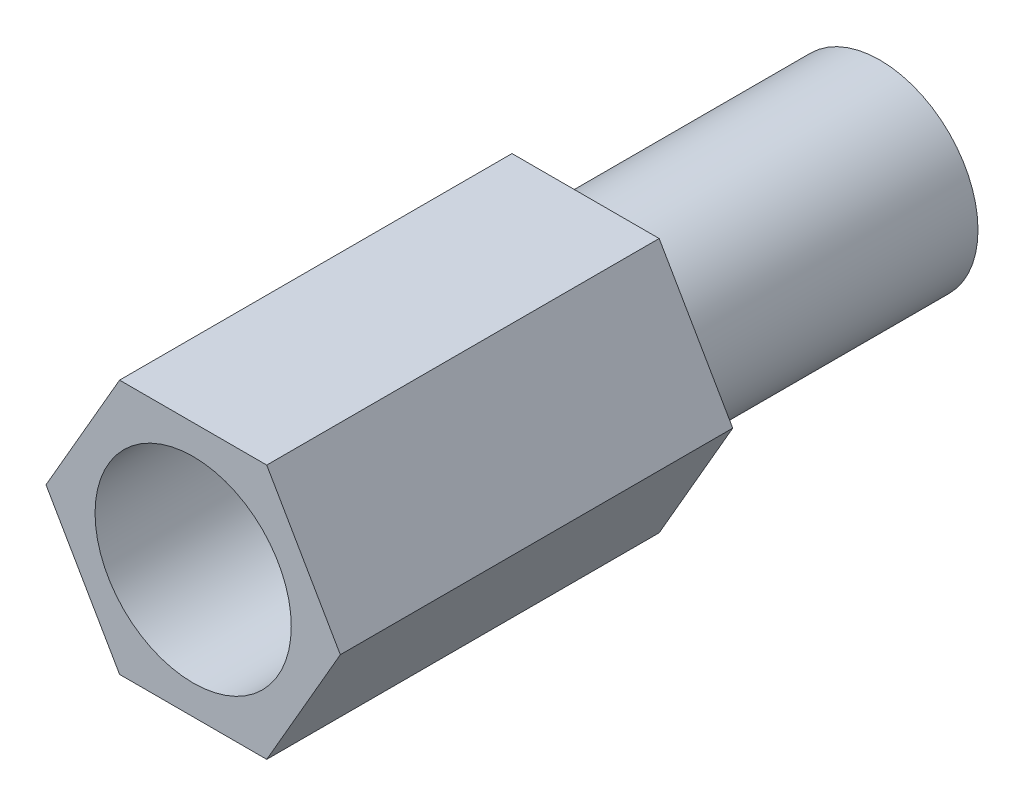
SolidWorks part; units mm, degrees
ref_plane "前视基准面" through (0, 0, 0) normal (0, 0, 1) x (1, 0, 0)
ref_plane "上视基准面" through (0, 0, 0) normal (0, 1, 0) x (1, 0, 0)
ref_plane "右视基准面" through (0, 0, 0) normal (1, 0, 0) x (0, 0, -1)
sketch "草图1" plane through (0, 0, 0) normal (0, 0, 1) x (1, 0, 0)
  line L1 (-1.5, 0) -> (-0.75, -1.299)
  line L2 (-0.75, -1.299) -> (0.75, -1.299)
  line L3 (0.75, -1.299) -> (1.5, 0)
  line L4 (1.5, 0) -> (0.75, 1.299)
  line L5 (0.75, 1.299) -> (-0.75, 1.299)
  line L6 (-0.75, 1.299) -> (-1.5, 0)
  circle A0 centre (0, 0) radius 1.299 construction
  circle A1 centre (0, 0) radius 1
  dimension "D1" = 2
  dimension "D2" = 3
extrude "凸台-拉伸1" add sketch "草图1" along normal blind 4
sketch "草图2" plane through (0, 0, 0) normal (0, 0, 1) x (1, 0, 0)
  circle A0 centre (0, 0) radius 1
extrude "凸台-拉伸2" add sketch "草图2" against normal blind 3 separate body
